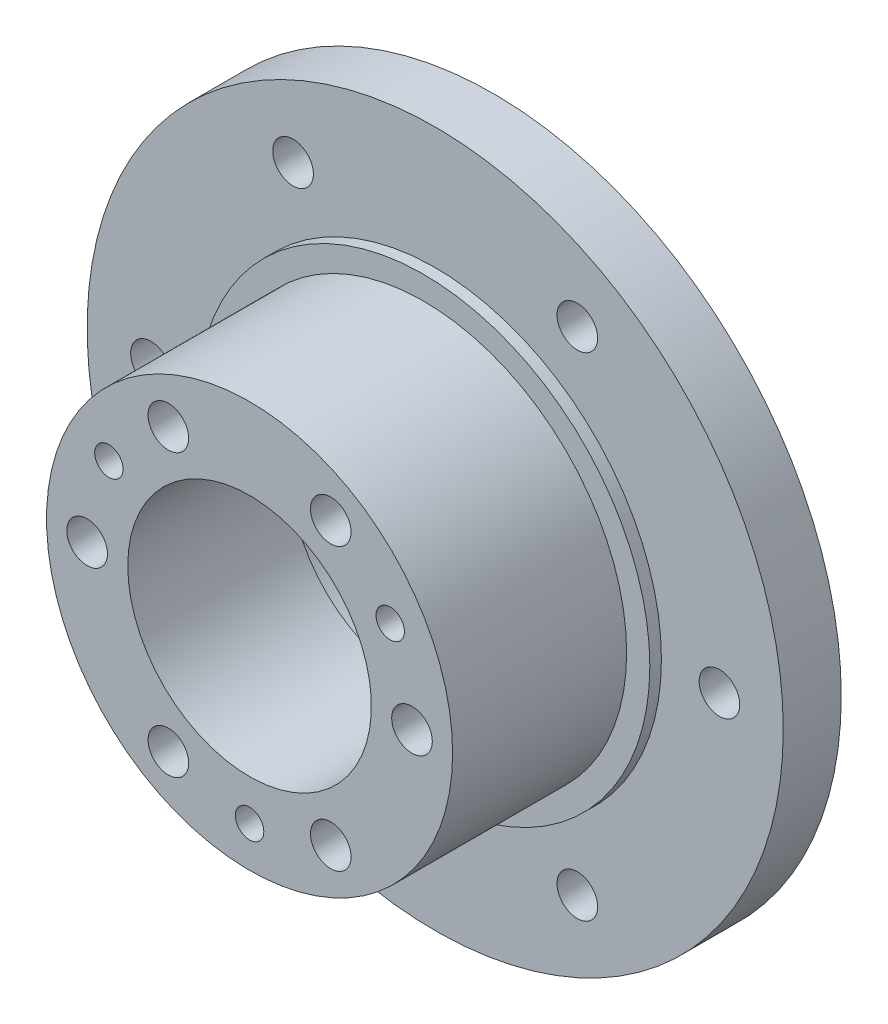
SolidWorks part; units mm, degrees
ref_plane "Front Plane" through (0, 0, 0) normal (0, 0, 1) x (1, 0, 0)
ref_plane "Top Plane" through (0, 0, 0) normal (0, 1, 0) x (1, 0, 0)
ref_plane "Right Plane" through (0, 0, 0) normal (1, 0, 0) x (0, 0, -1)
sketch "Sketch1" plane through (0, 0, 0) normal (0, 0, 1) x (1, 0, 0)
  circle A0 centre (0, 0) radius 30
  dimension "D1" = 60
extrude "Boss-Extrude1" add sketch "Sketch1" along normal blind 5
sketch "Sketch2" plane through (0, 0, 5) normal (0, 0, 1) x (1, 0, 0)
  circle A0 centre (0, 0) radius 19.5
  dimension "D1" = 39
extrude "Boss-Extrude2" add sketch "Sketch2" along normal blind 1
sketch "Sketch3" plane through (0, 0, 6) normal (0, 0, 1) x (1, 0, 0)
  circle A0 centre (0, 0) radius 17.5
  dimension "D1" = 35
extrude "Boss-Extrude3" add sketch "Sketch3" along normal blind 15
sketch "Sketch4" plane through (0, 0, 0) normal (0, 0, -1) x (-1, 0, 0)
  circle A0 centre (0, 0) radius 12.025
  dimension "D1" = 24.05
extrude "Cut-Extrude1" cut sketch "Sketch4" against normal blind 7 contours A0
sketch "Sketch5" plane through (0, 0, 7) normal (0, 0, -1) x (-1, 0, 0)
  circle A0 centre (0, 0) radius 10.5
  dimension "D1" = 21
extrude "Cut-Extrude2" cut sketch "Sketch5" against normal through all
sketch "Sketch6" plane through (0, 0, 5) normal (0, 0, 1) x (1, 0, 0)
  line L0 (0, 0) -> (33.6942, 0) construction
  circle A0 centre (0, 0) radius 24.5 construction
  circle A1 centre (24.5, 0) radius 1.75
  circle A2 centre (12.25, -21.2176) radius 1.75
  circle A3 centre (-12.25, -21.2176) radius 1.75
  circle A4 centre (-24.5, 0) radius 1.75
  circle A5 centre (-12.25, 21.2176) radius 1.75
  circle A6 centre (12.25, 21.2176) radius 1.75
  point P19 (0, 0)
  dimension "D1" = 49
  dimension "D2" = 3.5
  dimension "D3" = 6
extrude "Cut-Extrude3" cut sketch "Sketch6" against normal through all
sketch "Sketch7" plane through (0, 0, 21) normal (0, 0, 1) x (1, 0, 0)
  line L0 (0, 0) -> (34.5762, 0) construction
  circle A0 centre (0, 0) radius 14 construction
  circle A3 centre (14, 0) radius 1.75
  circle A5 centre (7, -12.1244) radius 1.75
  circle A6 centre (-7, -12.1244) radius 1.75
  circle A7 centre (-14, 0) radius 1.75
  circle A8 centre (-7, 12.1244) radius 1.75
  circle A9 centre (7, 12.1244) radius 1.75
  point P20 (0, 0)
  dimension "D1" = 28
  dimension "D2" = 3.5
  dimension "D3" = 6
extrude "Cut-Extrude4" cut sketch "Sketch7" against normal blind 10
sketch "Sketch8" plane through (0, 0, 21) normal (0, 0, 1) x (1, 0, 0)
  line L0 (0, 0) -> (28.2135, 16.2891) construction
  circle A0 centre (0, 0) radius 14 construction
  circle A1 centre (12.1244, 7) radius 1.225
  circle A2 centre (0, -14) radius 1.225
  circle A3 centre (-12.1244, 7) radius 1.225
  point P4 (12.1244, 7)
  point P15 (0, 0)
  dimension "D1" = 2.45
  dimension "D2" = 3
extrude "Cut-Extrude5" cut sketch "Sketch8" against normal blind 12
